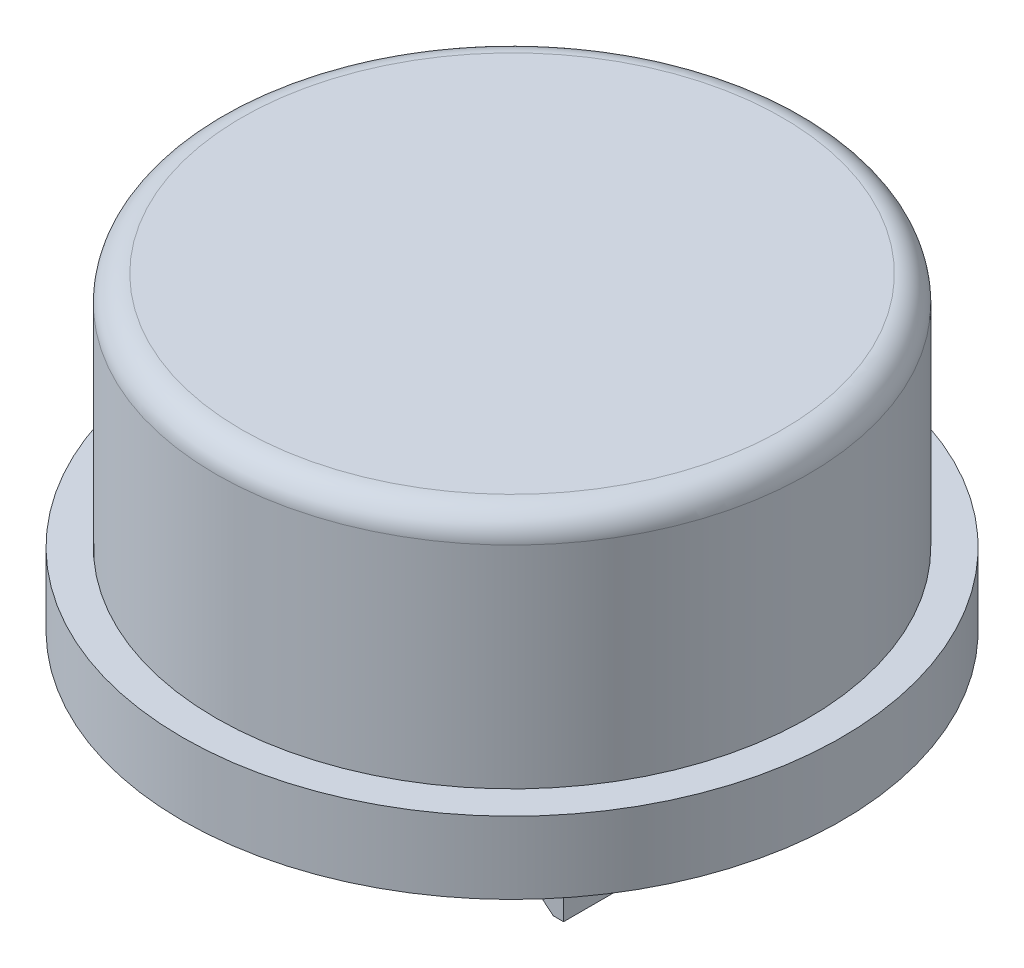
SolidWorks part; units mm, degrees
ref_plane "Front Plane" through (0, 0, 0) normal (0, 0, 1) x (1, 0, 0)
ref_plane "Top Plane" through (0, 0, 0) normal (0, 1, 0) x (1, 0, 0)
ref_plane "Right Plane" through (0, 0, 0) normal (1, 0, 0) x (0, 0, -1)
sketch "Sketch1" plane through (0, 0, 0) normal (0, 1, 0) x (1, 0, 0)
  circle A0 centre (0, 0) radius 5.75
  dimension "D1" = 11.5
extrude "Boss-Extrude1" add sketch "Sketch1" along normal blind 6
sketch "Sketch2" plane through (0, 0, 0) normal (0, 1, 0) x (1, 0, 0)
  circle A0 centre (0, 0) radius 6.4
  dimension "D1" = 12.8
extrude "Boss-Extrude2" add sketch "Sketch2" along normal blind 1.4
sketch "Sketch3" plane through (0, 0, 0) normal (0, 1, 0) x (1, 0, 0)
  circle A0 centre (0, 0) radius 4.9
  dimension "D1" = 9.8
extrude "Cut-Extrude1" cut sketch "Sketch3" along normal blind 5
sketch "Sketch4" plane through (0, 0, 0) normal (1, 0, 0) x (0, 0, -1)
  line L0 (0, 0) -> (0, 5) construction
  line L1 (-4.9, 5) -> (4.9, 5) construction
  line L2 (-6.4, 0) -> (6.4, 0) construction
  line L3 (2.8, 5) -> (2, 5)
  line L4 (2.8, 5) -> (2.8, -1.5)
  line L5 (2.8, -1.5) -> (2, -1.5)
  line L6 (2, 5) -> (2, -1.5)
  line L7 (-2, 5) -> (-2, -1.5)
  line L8 (-2.8, -1.5) -> (-2, -1.5)
  line L9 (-2.8, 5) -> (-2.8, -1.5)
  line L10 (-2.8, 5) -> (-2, 5)
  point P9 (2, 1.75)
  dimension "D1" = 2
  dimension "D2" = 0.8
  dimension "D3" = 1.5
extrude "Boss-Extrude3" add sketch "Sketch4" along normal mid plane 2
sketch "Sketch5" plane through (0, 0, 0) normal (0, 0, 1) x (1, 0, 0)
  line L0 (0, 0) -> (0, 5) construction
  line L1 (1, 5) -> (-1, 5) construction
  line L2 (-4.9, 5) -> (4.9, 5) construction
  line L3 (2.9, 5) -> (2, 5)
  line L4 (2.9, 5) -> (2.9, -2.5)
  line L6 (2, 5) -> (2, -0.9)
  line L7 (2.9, -2.5) -> (2.7, -2.5)
  line L9 (1.8, -1.4) -> (2, -0.9)
  line L10 (-6.4, 0) -> (6.4, 0) construction
  line L11 (-1.8, -1.4) -> (-2, -0.9)
  line L12 (-2.9, -2.5) -> (-2.7, -2.5)
  line L13 (-2, 5) -> (-2, -0.9)
  line L14 (-2.9, 5) -> (-2.9, -2.5)
  line L15 (-2.9, 5) -> (-2, 5)
  arc A0 (2.7, -2.5) -> (1.8, -1.4) centre (4.5058, -0.1044) cw
  arc A1 (-2.7, -2.5) -> (-1.8, -1.4) centre (-4.5058, -0.1044) ccw
  dimension "D8" = 3
  dimension "D1" = 2
  dimension "D2" = 0.9
  dimension "D3" = 2.5
  dimension "D4" = 1.6
  dimension "D5" = 0.2
  dimension "D6" = 0.5
  dimension "D7" = 0.2
extrude "Boss-Extrude4" add sketch "Sketch5" along normal mid plane 3.8
sketch "Sketch6" plane through (0, 5, 0) normal (0, -1, 0) x (1, 0, 0)
  line L0 (-2.9, 0.35) -> (-4.8875, 0.35)
  line L1 (-2.9, 1.9) -> (-2.9, -1.9) construction
  line L2 (0.35, 2.8) -> (0.35, 4.8875)
  line L3 (1, 2.8) -> (-1, 2.8) construction
  line L4 (-0.35, 4.8875) -> (-0.35, 2.8)
  line L5 (-0.35, 2.8) -> (0.35, 2.8)
  line L6 (1, 2.8) -> (-1, 2.8) construction
  line L7 (-2.9, 0.35) -> (-2.9, -0.35)
  line L8 (-2.9, 1.9) -> (-2.9, -1.9) construction
  line L9 (-2.9, -0.35) -> (-4.8875, -0.35)
  line L10 (2.9, -0.35) -> (4.8875, -0.35)
  line L11 (-0.35, -2.8) -> (-0.35, -4.8875)
  line L12 (0.35, -4.8875) -> (0.35, -2.8)
  line L13 (0.35, -2.8) -> (-0.35, -2.8)
  line L14 (2.9, -0.35) -> (2.9, 0.35)
  line L15 (2.9, 0.35) -> (4.8875, 0.35)
  arc A1 (-0.35, -4.8875) -> (0.35, -4.8875) centre (0, 0) ccw
  circle A2 centre (0, 0) radius 4.9
  arc A3 (-4.8875, 0.35) -> (-4.8875, -0.35) centre (0, 0) ccw
  arc A4 (4.8875, -0.35) -> (4.8875, 0.35) centre (0, 0) ccw
  arc A5 (0.35, 4.8875) -> (-0.35, 4.8875) centre (0, 0) ccw
  point P13 (-2.9, 0)
  point P14 (0, 2.8)
  point P17 (3.4781, 0.1187)
  point P22 (0, 0)
  point P31 (0, 0)
  dimension "D2" = 0.7
  dimension "D3" = 0.7
  dimension "D1" = 0
  dimension "D4" = 2
extrude "Boss-Extrude5" add sketch "Sketch6" along normal blind 4.5
fillet "Fillet1" radius 0.5 1 edges at (0, 6, 5.75)
